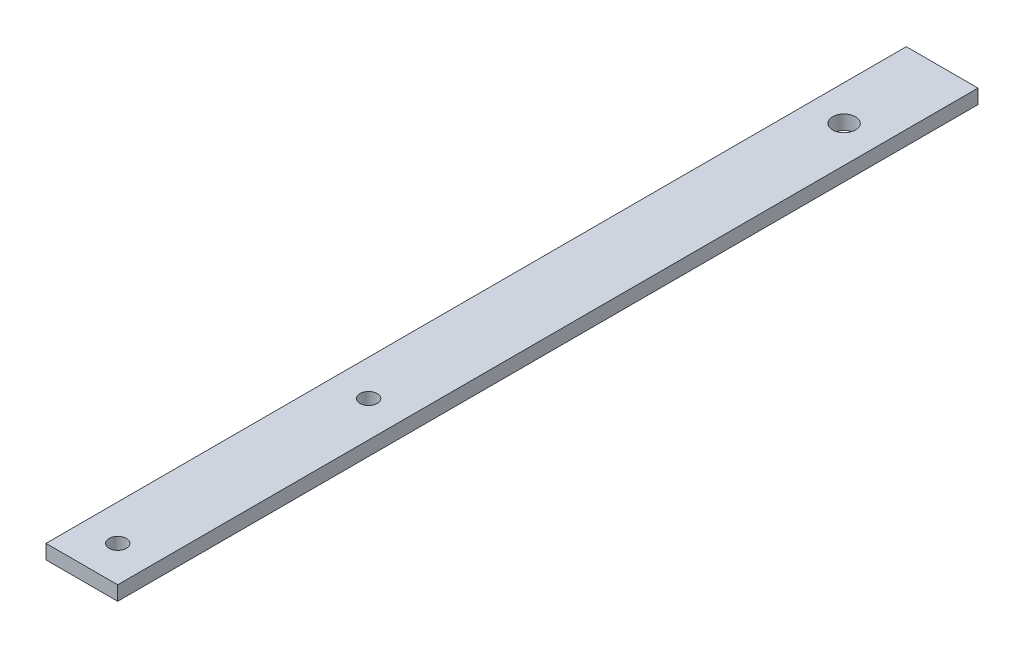
SolidWorks part; units mm, degrees
material "1060 Alloy"
ref_plane "Front Plane" through (0, 0, 0) normal (0, 0, 1) x (1, 0, 0)
ref_plane "Top Plane" through (0, 0, 0) normal (0, 1, 0) x (1, 0, 0)
ref_plane "Right Plane" through (0, 0, 0) normal (1, 0, 0) x (0, 0, -1)
sketch "Sketch1" plane through (0, 0, 0) normal (0, 1, 0) x (1, 0, 0)
  line L1 (0, 0) -> (25, 0)
  line L2 (0, 0) -> (0, 300)
  line L3 (0, 300) -> (25, 300)
  line L4 (25, 0) -> (25, 300)
  circle A0 centre (12.5, 12.5) radius 3
  circle A1 centre (12.5, 100) radius 3
  dimension "D2" = 6
  dimension "D6" = 6
  dimension "D1" = 25
  dimension "D3" = 12.5
  dimension "D4" = 12.5
  dimension "D5" = 300
  dimension "D7" = 200
  dimension "D8" = 12.5
extrude "Boss-Extrude1" add sketch "Sketch1" along normal blind 5
sketch "Sketch2" plane through (0, 5, 0) normal (0, 1, 0) x (1, 0, 0)
  line L0 (25, 0) -> (25, 300) construction
  line L1 (25, 300) -> (0, 300) construction
  circle A0 centre (12.3, 266) radius 4
  dimension "D1" = 8
  dimension "D2" = 12.7
  dimension "D3" = 34
extrude "Cut-Extrude1" cut sketch "Sketch2" against normal through all
